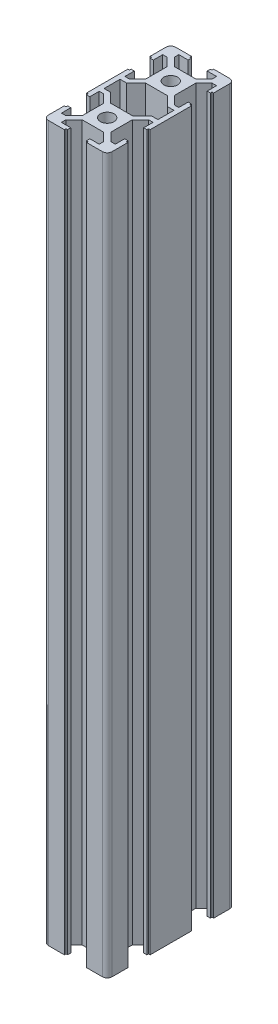
SolidWorks part; units mm, degrees
material "6063-T6"
ref_plane "Front Plane" through (0, 0, 0) normal (0, 0, 1) x (1, 0, 0)
ref_plane "Top Plane" through (0, 0, 0) normal (0, 1, 0) x (1, 0, 0)
ref_plane "Right Plane" through (0, 0, 0) normal (1, 0, 0) x (0, 0, -1)
sketch "Sketch1" plane through (0, 0, 0) normal (0, 0, 1) x (1, 0, 0)
  line L0 (0, 0) -> (0, 225)
  dimension "D1" = 225
other "20 series TS20-40B_5MM(1)"
ref_plane "Plane1" through (0, 0, 0) normal (0, 1, 0) x (-1, 0, 0)
sketch "Sketch22" plane through (0, 0, 0) normal (0, 1, 0) x (-1, 0, 0)
  line L6 (-9.5, 7) -> (-8.476, 7)
  line L7 (-9.5, 6.5) -> (-9.5, 7)
  line L8 (-10, 6.5) -> (-9.5, 6.5)
  line L9 (-8.476, 7) -> (-8.476, 4.05)
  line L10 (-9.5, 13.5) -> (-10, 13.5)
  line L11 (-9.5, 13) -> (-9.5, 13.5)
  line L12 (-8.476, 13) -> (-9.5, 13)
  line L13 (-8.476, 15.95) -> (-8.476, 13)
  line L14 (-10, 13.5) -> (-10, 18.5014)
  line L16 (-7.0636, 4.05) -> (-4.5, 6.6136)
  line L17 (-3.4583, 5.5) -> (-6.4323, 2.526)
  line L19 (3.4583, 5.5) -> (-3.4583, 5.5)
  line L21 (-4.5, 13.3864) -> (-7.0636, 15.95)
  line L23 (-4.5, 6.6136) -> (-4.5, 13.3864)
  line L25 (-3.3864, 14.5) -> (3.3864, 14.5)
  line L26 (-5.95, 18.476) -> (-5.95, 17.0636)
  line L27 (-3, 18.476) -> (-5.95, 18.476)
  line L28 (-3, 19.5) -> (-3, 18.476)
  line L29 (-3.5, 19.5) -> (-3, 19.5)
  line L30 (-3.5, 20) -> (-3.5, 19.5)
  line L31 (-5.95, 17.0636) -> (-3.3864, 14.5)
  line L33 (-8.476, 4.05) -> (-7.0636, 4.05)
  line L34 (-8.5014, 20) -> (-3.5, 20)
  line L35 (-7.0636, 15.95) -> (-8.476, 15.95)
  line L36 (-8.476, 2.526) -> (-6.4323, 2.526)
  line L39 (9.5, -7) -> (8.476, -7)
  line L40 (9.5, -6.5) -> (9.5, -7)
  line L41 (10, -6.5) -> (9.5, -6.5)
  line L42 (8.476, -7) -> (8.476, -4.05)
  line L43 (10, 6.5) -> (10, -6.5)
  line L44 (8.476, 2.526) -> (8.476, -2.526)
  line L45 (9.5, -13.5) -> (10, -13.5)
  line L46 (9.5, -13) -> (9.5, -13.5)
  line L47 (8.476, -13) -> (9.5, -13)
  line L48 (8.476, -15.95) -> (8.476, -13)
  line L49 (10, -13.5) -> (10, -18.5014)
  line L51 (7.0636, -4.05) -> (4.5, -6.6136)
  line L52 (3.4583, -5.5) -> (6.4323, -2.526)
  line L55 (4.5, -13.3864) -> (7.0636, -15.95)
  line L57 (4.5, -6.6136) -> (4.5, -13.3864)
  line L59 (5.95, -18.476) -> (5.95, -17.0636)
  line L60 (3, -18.476) -> (5.95, -18.476)
  line L61 (3, -19.5) -> (3, -18.476)
  line L62 (3.5, -19.5) -> (3, -19.5)
  line L63 (3.5, -20) -> (3.5, -19.5)
  line L64 (5.95, -17.0636) -> (3.3864, -14.5)
  line L66 (8.476, -4.05) -> (7.0636, -4.05)
  line L67 (8.5014, -20) -> (3.5, -20)
  line L68 (7.0636, -15.95) -> (8.476, -15.95)
  line L69 (8.476, -2.526) -> (6.4323, -2.526)
  line L70 (8.476, 2.526) -> (6.4323, 2.526)
  line L71 (7.0636, 15.95) -> (8.476, 15.95)
  line L72 (8.5014, 20) -> (3.5, 20)
  line L73 (8.476, 4.05) -> (7.0636, 4.05)
  line L75 (5.95, 17.0636) -> (3.3864, 14.5)
  line L76 (3.5, 20) -> (3.5, 19.5)
  line L77 (3.5, 19.5) -> (3, 19.5)
  line L78 (3, 19.5) -> (3, 18.476)
  line L79 (3, 18.476) -> (5.95, 18.476)
  line L80 (5.95, 18.476) -> (5.95, 17.0636)
  line L82 (4.5, 6.6136) -> (4.5, 13.3864)
  line L84 (4.5, 13.3864) -> (7.0636, 15.95)
  line L87 (3.4583, 5.5) -> (6.4323, 2.526)
  line L88 (7.0636, 4.05) -> (4.5, 6.6136)
  line L90 (10, 13.5) -> (10, 18.5014)
  line L91 (8.476, 15.95) -> (8.476, 13)
  line L92 (8.476, 13) -> (9.5, 13)
  line L93 (9.5, 13) -> (9.5, 13.5)
  line L94 (9.5, 13.5) -> (10, 13.5)
  line L95 (8.476, 7) -> (8.476, 4.05)
  line L96 (10, 6.5) -> (9.5, 6.5)
  line L97 (9.5, 6.5) -> (9.5, 7)
  line L98 (9.5, 7) -> (8.476, 7)
  line L99 (-8.476, -2.526) -> (-6.4323, -2.526)
  line L100 (-7.0636, -15.95) -> (-8.476, -15.95)
  line L101 (-8.5014, -20) -> (-3.5, -20)
  line L102 (-8.476, -4.05) -> (-7.0636, -4.05)
  line L104 (-5.95, -17.0636) -> (-3.3864, -14.5)
  line L105 (-3.5, -20) -> (-3.5, -19.5)
  line L106 (-3.5, -19.5) -> (-3, -19.5)
  line L107 (-3, -19.5) -> (-3, -18.476)
  line L108 (-3, -18.476) -> (-5.95, -18.476)
  line L109 (-5.95, -18.476) -> (-5.95, -17.0636)
  line L110 (-3.3864, -14.5) -> (3.3864, -14.5)
  line L112 (-4.5, -6.6136) -> (-4.5, -13.3864)
  line L114 (-4.5, -13.3864) -> (-7.0636, -15.95)
  line L116 (3.4583, -5.5) -> (-3.4583, -5.5)
  line L118 (-3.4583, -5.5) -> (-6.4323, -2.526)
  line L119 (-7.0636, -4.05) -> (-4.5, -6.6136)
  line L121 (-10, -13.5) -> (-10, -18.5014)
  line L122 (-8.476, -15.95) -> (-8.476, -13)
  line L123 (-8.476, -13) -> (-9.5, -13)
  line L124 (-9.5, -13) -> (-9.5, -13.5)
  line L125 (-9.5, -13.5) -> (-10, -13.5)
  line L126 (-8.476, 2.526) -> (-8.476, -2.526)
  line L127 (-10, 6.5) -> (-10, -6.5)
  line L128 (-8.476, -7) -> (-8.476, -4.05)
  line L129 (-10, -6.5) -> (-9.5, -6.5)
  line L130 (-9.5, -6.5) -> (-9.5, -7)
  line L131 (-9.5, -7) -> (-8.476, -7)
  arc A0 (-10, 18.5014) -> (-8.5014, 20) centre (-8.5014, 18.5014) cw
  circle A1 centre (0, 10) radius 2.15
  circle A2 centre (0, -10) radius 2.15
  arc A4 (10, -18.5014) -> (8.5014, -20) centre (8.5014, -18.5014) cw
  arc A7 (10, 18.5014) -> (8.5014, 20) centre (8.5014, 18.5014) ccw
  arc A11 (-10, -18.5014) -> (-8.5014, -20) centre (-8.5014, -18.5014) ccw
  point P0 (0, 0)
  point P1 (-10, 20)
  point P3 (0, 20)
  point P4 (10, 20)
  point P5 (10, 10)
  point P9 (10, 0)
  point P10 (10, -10)
  point P16 (0, 0)
  point P26 (10, -20)
  point P50 (0, -20)
  point P51 (-10, -20)
  point P52 (-10, -10)
  point P53 (-10, 0)
  point P54 (-10, 10)
  dimension "D1" = 4.3
  dimension "D2" = 4.3
hole_wizard "M6x1.0 Tapped Hole2" positions "Sketch23" profile "Sketch24" tap size "M6x1.0" standard "ANSI Metric"
sketch "Sketch23" plane through (0, 0, 0) normal (0, -1, 0) x (-1, 0, 0)
  point P0 (0, 10)
  point P3 (0, -10)
sketch "Sketch24" plane through (0, 0, -10) normal (1, 0, 0) x (0, 0, -1)
  line L0 (0, 0) -> (0, 16.5022)
  line L1 (0, 16.5022) -> (2.5, 15)
  line L2 (2.5, 15) -> (2.5, 0)
  line L5 (2.5, 0) -> (0, 0)
  line L10 (0, 16.5022) -> (-2.5, 15) construction
  line L11 (0, -6.35) -> (0, 107.95) construction
  dimension "Tap Drill Dia." = 5
  dimension "Tap Drill Depth" = 15
  dimension "Drill Angle" = 118
cosmetic thread "Hole Thread1" parameters "D1"=12, "D2"=6
cosmetic thread "Hole Thread2" parameters "D1"=12, "D2"=6
